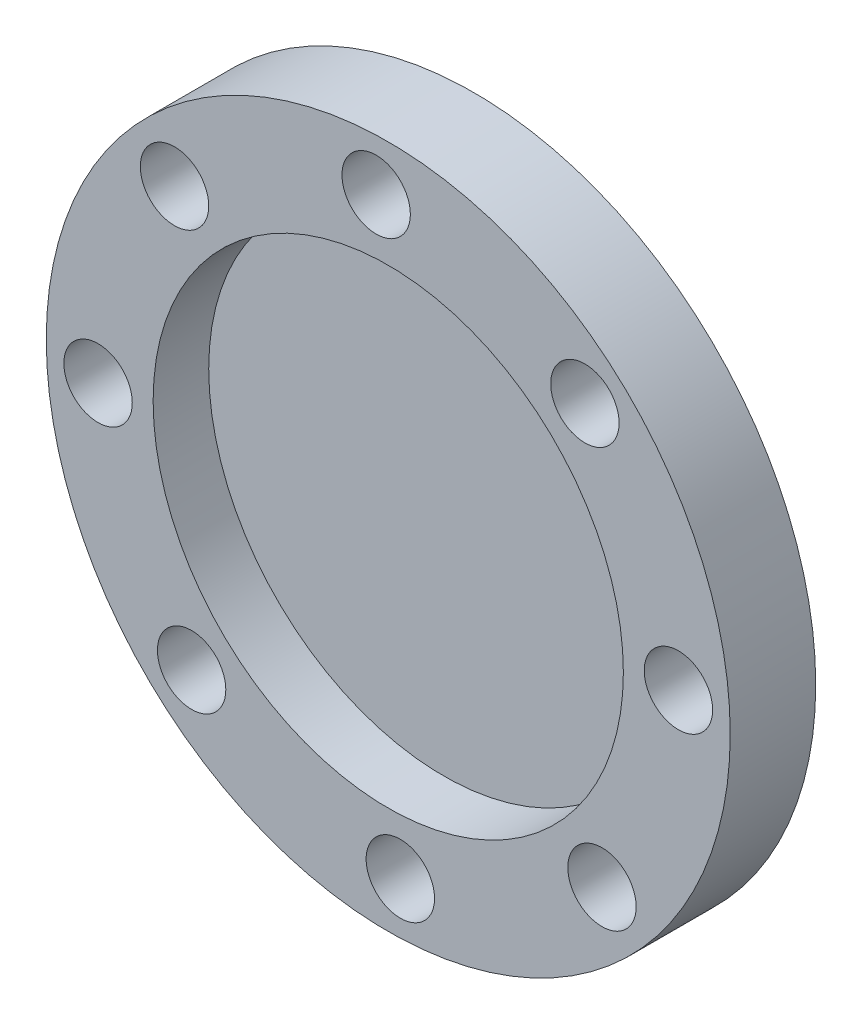
SolidWorks part; units mm, degrees
ref_plane "Front Plane" through (0, 0, 0) normal (0, 0, 1) x (1, 0, 0)
ref_plane "Top Plane" through (0, 0, 0) normal (0, 1, 0) x (1, 0, 0)
ref_plane "Right Plane" through (0, 0, 0) normal (1, 0, 0) x (0, 0, -1)
sketch "Sketch1" plane through (0, 0, 0) normal (0, 0, 1) x (1, 0, 0)
  circle A0 centre (0, 0) radius 40
  dimension "D1" = 80
extrude "Boss-Extrude1" add sketch "Sketch1" along normal blind 10
sketch "Sketch2" plane through (0, 0, 10) normal (0, 0, 1) x (1, 0, 0)
  circle A0 centre (0, 0) radius 27.5
  dimension "D1" = 55
extrude "Cut-Extrude1" cut sketch "Sketch2" against normal blind 6.5
sketch "Sketch3" plane through (0, 0, 10) normal (0, 0, 1) x (1, 0, 0)
  circle A2 centre (-25, 23) radius 4
  circle A10 centre (0, 0) radius 33.75
  circle A11 centre (-1.4142, 33.9411) radius 4
  circle A12 centre (23, 25) radius 4
  circle A13 centre (33.9411, 1.4142) radius 4
  circle A14 centre (25, -23) radius 4
  circle A15 centre (1.4142, -33.9411) radius 4
  circle A16 centre (-23, -25) radius 4
  circle A17 centre (-33.9411, -1.4142) radius 4
  point P20 (0, 0)
  point P22 (0, 0)
  dimension "D1" = 8
  dimension "D2" = 67.5
  dimension "D3" = 25
  dimension "D4" = 23
  dimension "D5" = 8
extrude "Cut-Extrude2" cut sketch "Sketch3" against normal through all contours A10 A11 | A2 | A17 | A16 | A15 | A14 | A13 | A12
cosmetic thread "Cosmetic Thread1" parameters "D2"=10
cosmetic thread "Cosmetic Thread2" parameters "D2"=10
cosmetic thread "Cosmetic Thread3" parameters "D2"=10
cosmetic thread "Cosmetic Thread4" parameters "D2"=10
cosmetic thread "Cosmetic Thread5" parameters "D2"=10
cosmetic thread "Cosmetic Thread6" parameters "D2"=10
cosmetic thread "Cosmetic Thread7" parameters "D2"=10
